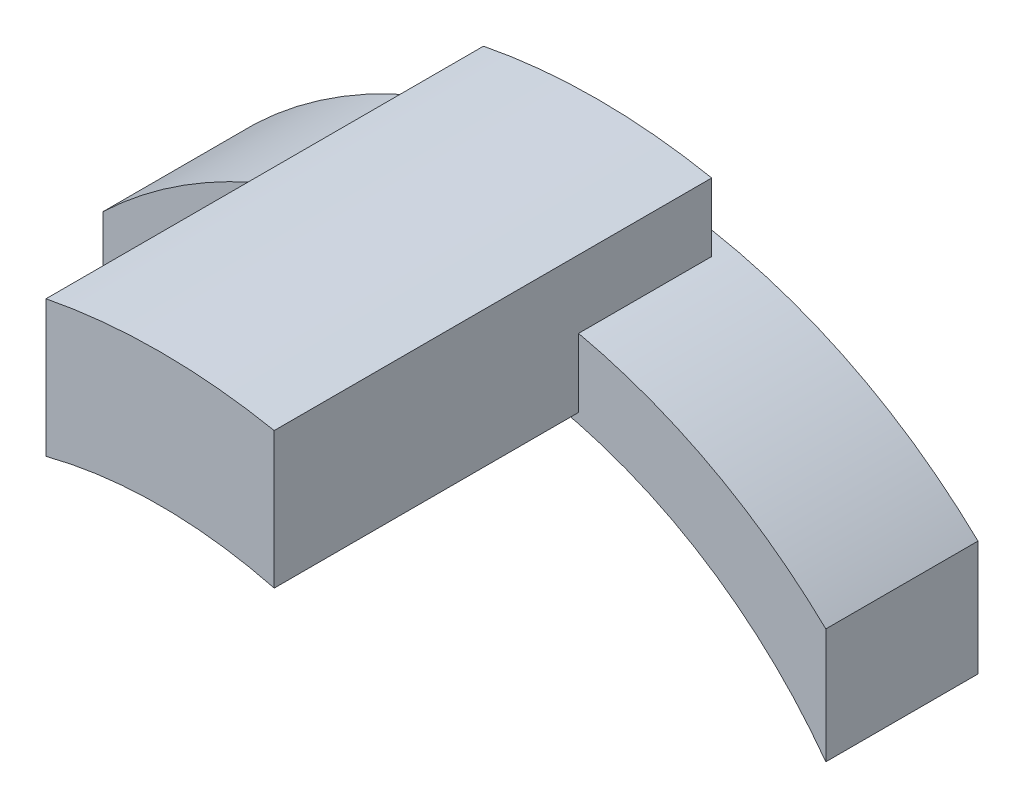
SolidWorks part; units mm, degrees
ref_plane "Front Plane" through (0, 0, 0) normal (0, 0, 1) x (1, 0, 0)
ref_plane "Top Plane" through (0, 0, 0) normal (0, 1, 0) x (1, 0, 0)
ref_plane "Right Plane" through (0, 0, 0) normal (1, 0, 0) x (0, 0, -1)
sketch "Sketch1" plane through (0, 0, 0) normal (0, 0, 1) x (1, 0, 0)
  line L0 (-19, 13.8293) -> (-19, 19.8809)
  line L1 (19, 19.8809) -> (19, 13.8293)
  arc A0 (19, 13.8293) -> (-19, 13.8293) centre (0, 0) ccw
  arc A1 (19, 19.8809) -> (-19, 19.8809) centre (0, 0) ccw
  dimension "D1" = 47
  dimension "D3" = 4
  dimension "D2" = 38
extrude "Extrude1" add sketch "Sketch1" along normal mid plane 8
sketch "Sketch2" plane through (0, 0, 4) normal (0, 0, -1) x (-1, 0, 0)
  line L0 (6, 23.2379) -> (6, 30.4138)
  line L1 (-6, 30.4138) -> (-6, 23.2379)
  arc A0 (6, 30.4138) -> (-6, 30.4138) centre (0, 0) ccw
  arc A2 (6, 23.2379) -> (-6, 23.2379) centre (0, 0) ccw
  arc A3 (19, 13.8293) -> (-19, 13.8293) centre (0, 0) ccw construction
  dimension "D2" = 7
  dimension "D3" = 0.5
  dimension "D1" = 12
extrude "Extrude2" add sketch "Sketch2" against normal blind 16 and the other way blind 7
